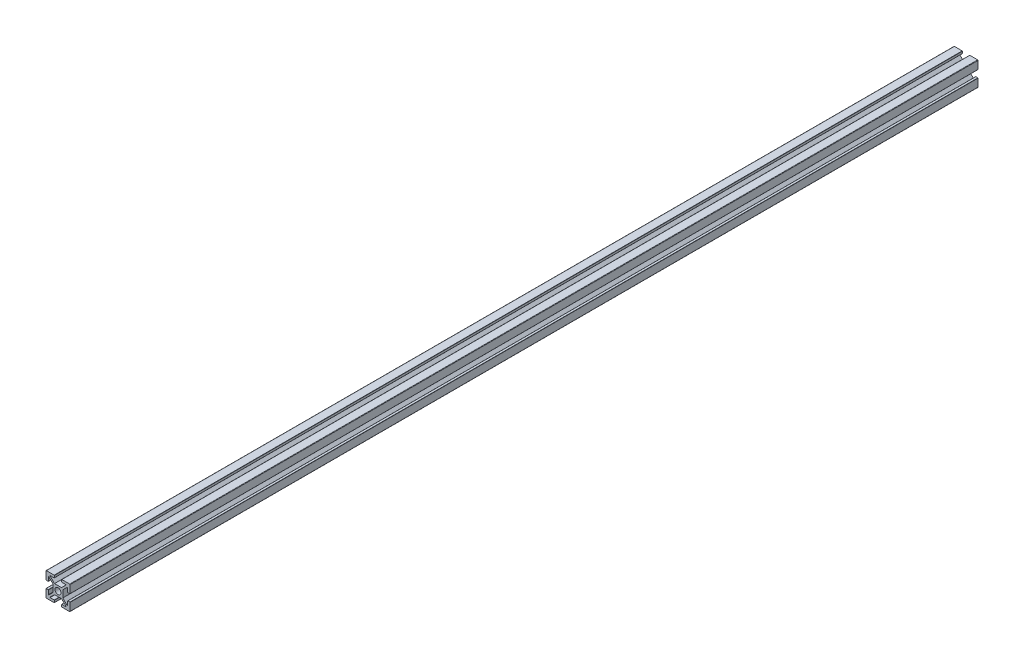
SolidWorks part; units mm, degrees
ref_plane "Front Plane" through (0, 0, 0) normal (0, 0, 1) x (1, 0, 0)
ref_plane "Top Plane" through (0, 0, 0) normal (0, 1, 0) x (1, 0, 0)
ref_plane "Right Plane" through (0, 0, 0) normal (1, 0, 0) x (0, 0, -1)
sketch "Sketch1" plane through (0, 0, 0) normal (0, 0, 1) x (1, 0, 0)
  line L0 (-31.3764, -0.0618) -> (-29.6764, -0.0618)
  line L1 (-24.6764, 6.9382) -> (-31.1764, 6.9382)
  line L2 (-31.5264, 0.0882) -> (-31.5264, 6.5882)
  line L3 (-18.5469, 0.9382) -> (-24.4133, 0.9382)
  line L4 (-25.4801, -6.0072) -> (-25.4801, -0.1164)
  line L5 (-29.5264, 0.0882) -> (-29.5264, 3.5244)
  line L6 (-28.0945, 4.9382) -> (-24.6764, 4.9382)
  line L7 (-24.5264, 5.0882) -> (-24.5264, 6.7882)
  line L8 (-29.5264, 4.9382) -> (-25.4801, 0.9382) construction
  line L9 (-29.271, 3.631) -> (-25.4801, -0.1164)
  line L10 (-28.1999, 4.6815) -> (-24.4133, 0.9382)
  line L11 (-13.4338, 4.9382) -> (-17.4801, 0.9382) construction
  line L12 (-21.4801, -3.0618) -> (-21.4801, 8.6268) construction
  line L13 (-21.4801, -3.0618) -> (-36.4642, -3.0618) construction
  line L14 (-14.7603, 4.6815) -> (-18.5469, 0.9382)
  line L15 (-13.6893, 3.631) -> (-17.4801, -0.1164)
  line L16 (-18.4338, 5.0882) -> (-18.4338, 6.7882)
  line L17 (-14.8657, 4.9382) -> (-18.2838, 4.9382)
  line L18 (-13.4338, 0.0882) -> (-13.4338, 3.5244)
  line L19 (-17.4801, -6.0072) -> (-17.4801, -0.1164)
  line L20 (-11.4338, 0.0882) -> (-11.4338, 6.5882)
  line L21 (-18.2838, 6.9382) -> (-11.7838, 6.9382)
  line L22 (-11.5838, -0.0618) -> (-13.2838, -0.0618)
  line L23 (-13.4338, -11.0618) -> (-17.4801, -7.0618) construction
  line L24 (-29.5264, -11.0618) -> (-25.4801, -7.0618) construction
  line L25 (-11.5838, -6.0618) -> (-13.2838, -6.0618)
  line L26 (-18.2838, -13.0618) -> (-11.7838, -13.0618)
  line L27 (-11.4338, -6.2118) -> (-11.4338, -12.7118)
  line L28 (-13.4338, -6.2118) -> (-13.4338, -9.648)
  line L29 (-14.8657, -11.0618) -> (-18.2838, -11.0618)
  line L30 (-18.4338, -11.2118) -> (-18.4338, -12.9118)
  line L31 (-13.6893, -9.7547) -> (-17.4801, -6.0072)
  line L32 (-14.7603, -10.8051) -> (-18.5469, -7.0618)
  line L33 (-28.1999, -10.8051) -> (-24.4133, -7.0618)
  line L34 (-29.271, -9.7547) -> (-25.4801, -6.0072)
  line L35 (-24.5264, -11.2118) -> (-24.5264, -12.9118)
  line L36 (-28.0945, -11.0618) -> (-24.6764, -11.0618)
  line L37 (-29.5264, -6.2118) -> (-29.5264, -9.648)
  line L38 (-18.5469, -7.0618) -> (-24.4133, -7.0618)
  line L39 (-31.5264, -6.2118) -> (-31.5264, -12.7118)
  line L40 (-24.6764, -13.0618) -> (-31.1764, -13.0618)
  line L41 (-31.3764, -6.0618) -> (-29.6764, -6.0618)
  circle A0 centre (-21.4801, -3.0618) radius 2.5
  arc A1 (-31.5264, 6.5882) -> (-31.1764, 6.9382) centre (-31.1764, 6.5882) cw
  arc A2 (-31.3764, -0.0618) -> (-31.5264, 0.0882) centre (-31.3764, 0.0882) cw
  arc A3 (-29.6764, -0.0618) -> (-29.5264, 0.0882) centre (-29.6764, 0.0882) ccw
  arc A4 (-24.6764, 6.9382) -> (-24.5264, 6.7882) centre (-24.6764, 6.7882) cw
  arc A5 (-24.6764, 4.9382) -> (-24.5264, 5.0882) centre (-24.6764, 5.0882) ccw
  arc A6 (-28.1999, 4.6815) -> (-28.0945, 4.9382) centre (-28.0945, 4.7882) cw
  arc A7 (-29.271, 3.631) -> (-29.5264, 3.5244) centre (-29.3764, 3.5244) ccw
  arc A8 (-13.6893, 3.631) -> (-13.4338, 3.5244) centre (-13.5838, 3.5244) cw
  arc A9 (-14.7603, 4.6815) -> (-14.8657, 4.9382) centre (-14.8657, 4.7882) ccw
  arc A10 (-18.2838, 4.9382) -> (-18.4338, 5.0882) centre (-18.2838, 5.0882) cw
  arc A11 (-18.2838, 6.9382) -> (-18.4338, 6.7882) centre (-18.2838, 6.7882) ccw
  arc A12 (-13.2838, -0.0618) -> (-13.4338, 0.0882) centre (-13.2838, 0.0882) cw
  arc A13 (-11.5838, -0.0618) -> (-11.4338, 0.0882) centre (-11.5838, 0.0882) ccw
  arc A14 (-11.4338, 6.5882) -> (-11.7838, 6.9382) centre (-11.7838, 6.5882) ccw
  arc A15 (-11.4338, -12.7118) -> (-11.7838, -13.0618) centre (-11.7838, -12.7118) cw
  arc A16 (-11.5838, -6.0618) -> (-11.4338, -6.2118) centre (-11.5838, -6.2118) cw
  arc A17 (-13.2838, -6.0618) -> (-13.4338, -6.2118) centre (-13.2838, -6.2118) ccw
  arc A18 (-18.2838, -13.0618) -> (-18.4338, -12.9118) centre (-18.2838, -12.9118) cw
  arc A19 (-18.2838, -11.0618) -> (-18.4338, -11.2118) centre (-18.2838, -11.2118) ccw
  arc A20 (-14.7603, -10.8051) -> (-14.8657, -11.0618) centre (-14.8657, -10.9118) cw
  arc A21 (-13.6893, -9.7547) -> (-13.4338, -9.648) centre (-13.5838, -9.648) ccw
  arc A22 (-29.271, -9.7547) -> (-29.5264, -9.648) centre (-29.3764, -9.648) cw
  arc A23 (-28.1999, -10.8051) -> (-28.0945, -11.0618) centre (-28.0945, -10.9118) ccw
  arc A24 (-24.6764, -11.0618) -> (-24.5264, -11.2118) centre (-24.6764, -11.2118) cw
  arc A25 (-24.6764, -13.0618) -> (-24.5264, -12.9118) centre (-24.6764, -12.9118) ccw
  arc A26 (-29.6764, -6.0618) -> (-29.5264, -6.2118) centre (-29.6764, -6.2118) cw
  arc A27 (-31.3764, -6.0618) -> (-31.5264, -6.2118) centre (-31.3764, -6.2118) ccw
  arc A28 (-31.5264, -12.7118) -> (-31.1764, -13.0618) centre (-31.1764, -12.7118) ccw
  point P27 (-18.4338, 4.9382)
  point P28 (-11.4338, -13.0618)
  point P47 (-17.4801, -3.0618)
  point P57 (-21.4801, 0.9382)
  point P59 (-18.4338, 6.9382)
  point P60 (-13.4338, -0.0618)
  point P61 (-11.4338, -0.0618)
  point P62 (-11.4338, 6.9382)
  point P112 (-25.4801, -3.0618)
  point P113 (-11.4338, -6.0618)
  point P114 (-13.4338, -6.0618)
  point P115 (-18.4338, -13.0618)
  point P116 (-21.4801, -7.0618)
  point P117 (-24.5264, -11.0618)
  point P118 (-24.5264, -13.0618)
  point P119 (-29.5264, -6.0618)
  point P120 (-18.4338, -11.0618)
  point P121 (-31.5264, -6.0618)
  point P122 (-31.5264, -13.0618)
  dimension "D3" = 0.35
  dimension "D4" = 0.15
  dimension "D5" = 0.15
  dimension "D6" = 0.15
  dimension "D7" = 0.15
  dimension "D8" = 0.15
  dimension "D9" = 0.15
  dimension "D1" = 0.75
  dimension "D2" = 0.75
extrude "Boss-Extrude1" add sketch "Sketch1" along normal blind 760
